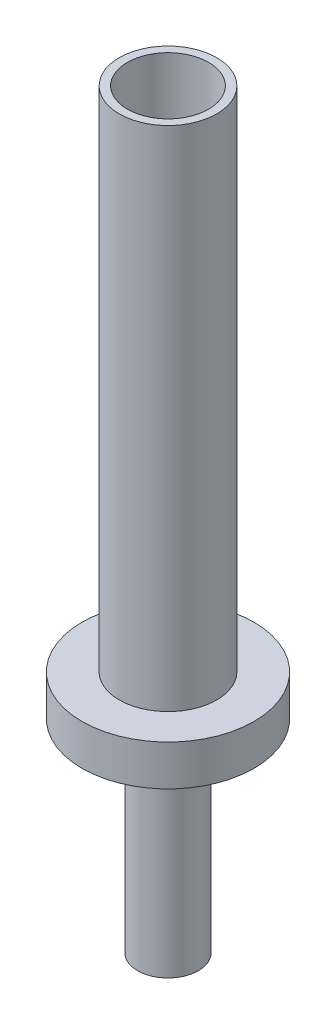
SolidWorks part; units mm, degrees
ref_plane "Front Plane" through (0, 0, 0) normal (0, 0, 1) x (1, 0, 0)
ref_plane "Top Plane" through (0, 0, 0) normal (0, 1, 0) x (1, 0, 0)
ref_plane "Right Plane" through (0, 0, 0) normal (1, 0, 0) x (0, 0, -1)
sketch "Sketch1" plane through (0, 0, 0) normal (0, 1, 0) x (1, 0, 0)
  circle A0 centre (0, 0) radius 7.5
  dimension "D1" = 15
extrude "Boss-Extrude1" add sketch "Sketch1" along normal blind 50
sketch "Sketch2" plane through (0, 50, 0) normal (0, 1, 0) x (1, 0, 0)
  circle A0 centre (0, 0) radius 21.1839
extrude "Boss-Extrude2" add sketch "Sketch2" along normal blind 10
sketch "Sketch3" plane through (0, 60, 0) normal (0, 1, 0) x (1, 0, 0)
  circle A0 centre (0, 0) radius 10
  circle A1 centre (0, 0) radius 12
  dimension "D1" = 20
  dimension "D2" = 24
extrude "Boss-Extrude3" add sketch "Sketch3" along normal blind 125
